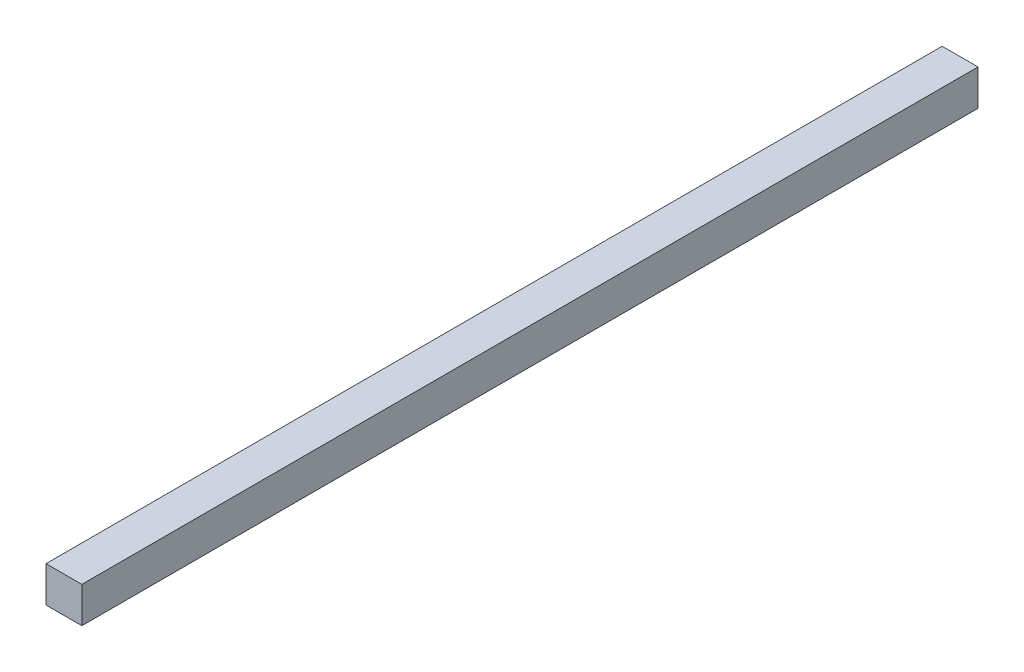
SolidWorks part; units mm, degrees
ref_plane "Front Plane" through (0, 0, 0) normal (0, 0, 1) x (1, 0, 0)
ref_plane "Top Plane" through (0, 0, 0) normal (0, 1, 0) x (1, 0, 0)
ref_plane "Right Plane" through (0, 0, 0) normal (1, 0, 0) x (0, 0, -1)
sketch "Sketch1" plane through (0, 0, 0) normal (0, 0, 1) x (1, 0, 0)
  line L1 (1.6, 1.6) -> (-1.6, 1.6)
  line L2 (1.6, 1.6) -> (1.6, -1.6)
  line L3 (1.6, -1.6) -> (-1.6, -1.6)
  line L4 (-1.6, 1.6) -> (-1.6, -1.6)
  line L5 (1.6, 1.6) -> (-1.6, -1.6) construction
  line L6 (1.6, -1.6) -> (-1.6, 1.6) construction
  point P0 (0, 0)
  dimension "D1" = 3.2
extrude "Boss-Extrude1" add sketch "Sketch1" along normal blind 80
